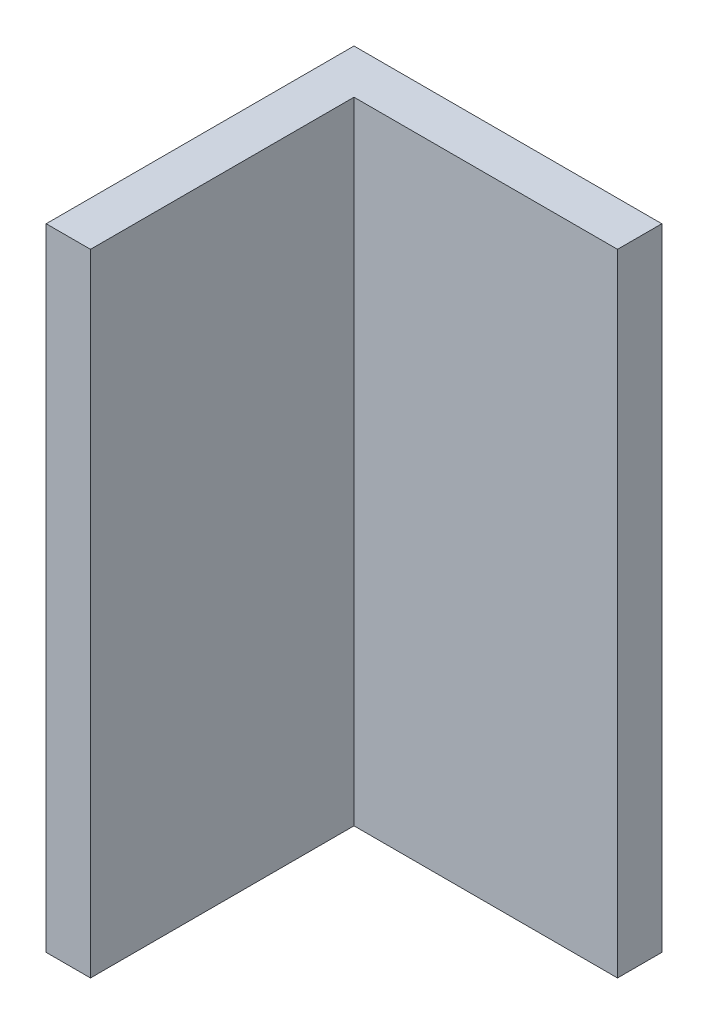
SolidWorks part; units mm, degrees
material "6061 Alloy"
ref_plane "Front Plane" through (0, 0, 0) normal (0, 0, 1) x (1, 0, 0)
ref_plane "Top Plane" through (0, 0, 0) normal (0, 1, 0) x (1, 0, 0)
ref_plane "Right Plane" through (0, 0, 0) normal (1, 0, 0) x (0, 0, -1)
sketch "Sketch2" plane through (0, 0, 0) normal (0, 1, 0) x (1, 0, 0)
  line L1 (0, 0) -> (25.4, 0)
  line L2 (0, 0) -> (0, -25.4)
  line L3 (0, -25.4) -> (25.4, -25.4)
  line L4 (25.4, 0) -> (25.4, -25.4)
extrude "Boss-Extrude1" add sketch "Sketch2" along normal blind 52.07
sketch "Sketch3" plane through (0, 52.07, 0) normal (0, 1, 0) x (1, 0, 0)
  line L0 (25.4, -25.4) -> (25.4, 0) construction
  line L1 (25.4, -3.6576) -> (3.6576, -3.6576)
  line L2 (25.4, -3.6576) -> (25.4, -25.4)
  line L3 (25.4, -25.4) -> (3.6576, -25.4)
  line L4 (3.6576, -3.6576) -> (3.6576, -25.4)
  line L5 (0, -25.4) -> (25.4, -25.4) construction
  line L6 (0, 0) -> (0, -25.4) construction
  line L7 (25.4, 0) -> (0, 0) construction
  dimension "D1" = 3.6576
  dimension "D2" = 3.6576
extrude "Cut-Extrude1" cut sketch "Sketch3" against normal blind 52.07
